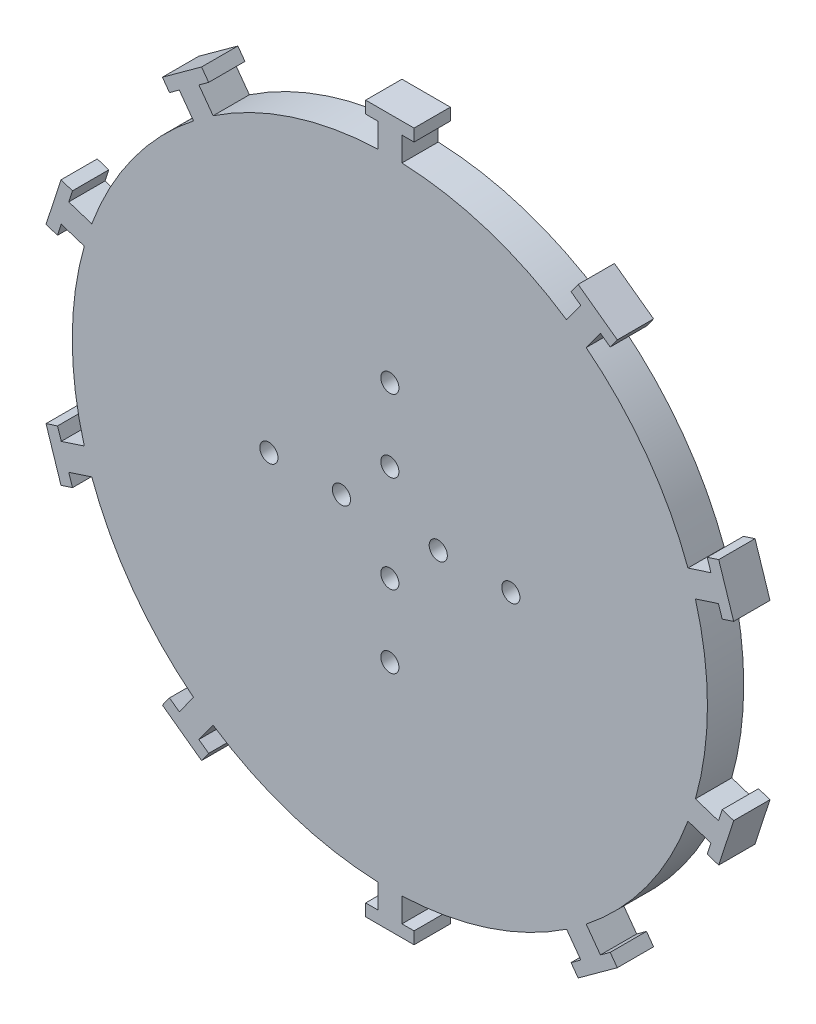
SolidWorks part; units mm, degrees
ref_plane "Front Plane" through (0, 0, 0) normal (0, 0, 1) x (1, 0, 0)
ref_plane "Top Plane" through (0, 0, 0) normal (0, 1, 0) x (1, 0, 0)
ref_plane "Right Plane" through (0, 0, 0) normal (1, 0, 0) x (0, 0, -1)
sketch "Sketch1" plane through (0, 0, 0) normal (0, 0, 1) x (1, 0, 0)
  circle A0 centre (0, 0) radius 52.5
  dimension "D1" = 105
extrude "Boss-Extrude1" add sketch "Sketch1" along normal blind 2
sketch "Sketch6" plane through (0, 0, 0) normal (0, 0, 1) x (1, 0, 0)
  line L0 (-2, 52.4619) -> (-2, 56.4619)
  line L1 (0, 37.6165) -> (0, 55.5597) construction
  line L2 (2, 52.4619) -> (2, 56.4619)
  line L3 (-2, 56.4619) -> (-4, 56.4619)
  line L4 (-4, 56.4619) -> (-4, 58.4619)
  line L5 (-4, 58.4619) -> (4, 58.4619)
  line L6 (4, 58.4619) -> (4, 56.4619)
  line L7 (4, 56.4619) -> (2, 56.4619)
  circle A0 centre (0, 0) radius 52.5 construction
  circle A2 centre (0, 0) radius 52.5
  arc A3 (-2, 52.4619) -> (2, 52.4619) centre (0, 0) ccw
  dimension "D1" = 4
  dimension "D2" = 4
  dimension "D3" = 2
  dimension "D4" = 2
  dimension "D5" = 0
extrude "Boss-Extrude2" add sketch "Sketch6" along normal blind 6
pattern_circular "CirPattern1" count 10 over 360 about axis through (0, 0, 0) along (0, 0, 1) of "Boss-Extrude2"
sketch "Sketch4" plane through (0, 0, 2) normal (0, 0, 1) x (1, 0, 0)
  line L0 (0, -55) -> (0, 55) construction
  circle A0 centre (0, 8) radius 1.5
  circle A4 centre (8, 0) radius 1.5
  circle A5 centre (0, -8) radius 1.5
  circle A6 centre (-8, 0) radius 1.5
  point P15 (0, 0)
  dimension "D1" = 3
  dimension "D2" = 8
  dimension "D3" = 4
extrude "Cut-Extrude2" cut sketch "Sketch4" against normal mid plane 20
sketch "Sketch7" plane through (0, 0, 6) normal (0, 0, 1) x (1, 0, 0)
  circle A0 centre (0, 20) radius 1.5
  circle A1 centre (20, 0) radius 1.5
  circle A2 centre (0, -20) radius 1.5
  circle A3 centre (-20, 0) radius 1.5
  point P12 (0, 0)
  dimension "D1" = 3
  dimension "D2" = 20
  dimension "D3" = 4
extrude "Cut-Extrude3" cut sketch "Sketch7" against normal mid plane 20
equation "\"diameter\"=80"
equation "\"D1\" = \"diameter\" / 2"
